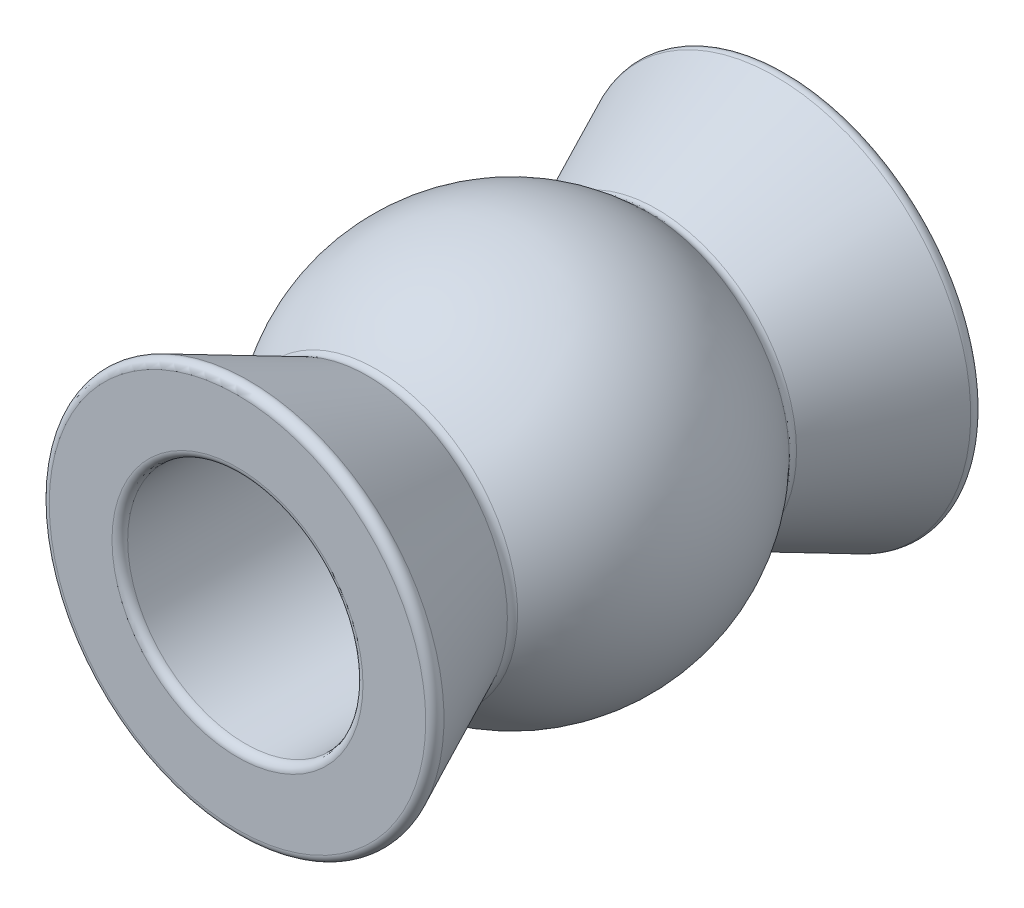
SolidWorks part; units mm, degrees
ref_plane "Front Plane" through (0, 0, 0) normal (0, 0, 1) x (1, 0, 0)
ref_plane "Top Plane" through (0, 0, 0) normal (0, 1, 0) x (1, 0, 0)
ref_plane "Right Plane" through (0, 0, 0) normal (1, 0, 0) x (0, 0, -1)
sketch "Sketch1" plane through (0, 0, 0) normal (1, 0, 0) x (0, 0, -1)
  line L0 (-3.5, 2.4) -> (-3.5, 1.6)
  line L1 (-3.4, 1.5) -> (3.4, 1.5)
  line L2 (-3.3577, 2.4906) -> (-1.8434, 1.7845)
  line L3 (0, 2.75) -> (0, -2.75) construction
  line L4 (3.3577, 2.4906) -> (1.8434, 1.7845)
  line L5 (3.5, 2.4) -> (3.5, 1.6)
  line L6 (0, 0) -> (-3.5, 0) construction
  arc A0 (1.7318, 1.803) -> (-1.7318, 1.803) centre (0, 0) ccw
  arc A1 (-3.5, 2.4) -> (-3.3577, 2.4906) centre (-3.4, 2.4) cw
  arc A2 (-3.5, 1.6) -> (-3.4, 1.5) centre (-3.4, 1.6) ccw
  arc A3 (-1.8434, 1.7845) -> (-1.7318, 1.803) centre (-1.8011, 1.8751) ccw
  arc A4 (1.8434, 1.7845) -> (1.7318, 1.803) centre (1.8011, 1.8751) cw
  arc A5 (3.5, 2.4) -> (3.3577, 2.4906) centre (3.4, 2.4) ccw
  arc A6 (3.5, 1.6) -> (3.4, 1.5) centre (3.4, 1.6) cw
  point P24 (-3.4, 2.5)
  dimension "D1" = 5
  dimension "D2" = 0.1
  dimension "D3" = 0.1
  dimension "D4" = 7
  dimension "D5" = 2.5
  dimension "D6" = 1.5
  dimension "D7" = 130
revolve "Revolve1" add sketch "Sketch1" angle 360 about L6
